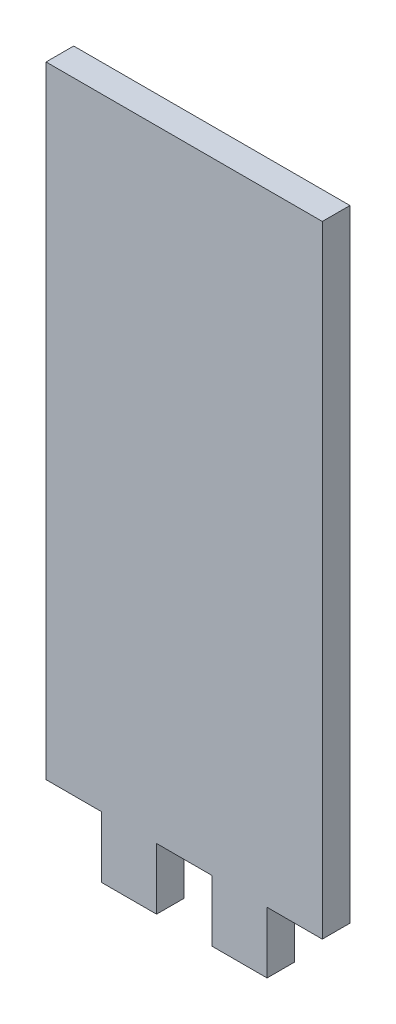
SolidWorks part; units mm, degrees
material "Акрил (Средняя-высокая ударопрочность)"
ref_plane "Спереди" through (0, 0, 0) normal (0, 0, 1) x (1, 0, 0)
ref_plane "Сверху" through (0, 0, 0) normal (0, 1, 0) x (1, 0, 0)
ref_plane "Справа" through (0, 0, 0) normal (1, 0, 0) x (0, 0, -1)
other "Configuration Table"
sketch "Эскиз1" plane through (0, 0, 0) normal (0, 0, 1) x (1, 0, 0)
  line L1 (10, -22.5) -> (6, -22.5)
  line L2 (10, -22.5) -> (10, 22.5)
  line L3 (10, 22.5) -> (-10, 22.5)
  line L4 (-10, -22.5) -> (-10, 22.5)
  line L5 (10, -22.5) -> (-10, 22.5) construction
  line L6 (10, 22.5) -> (-10, -22.5) construction
  line L11 (-6, -22.5) -> (-6, -26.9352)
  line L12 (-2, -26.9352) -> (-2, -22.5)
  line L16 (-6, -22.5) -> (-10, -22.5)
  line L17 (-2, -22.5) -> (2, -22.5)
  line L18 (2, -22.5) -> (2, -26.9352)
  line L19 (2, -26.9352) -> (6, -26.9352)
  line L20 (6, -26.9352) -> (6, -22.5)
  line L22 (-6, -26.9352) -> (-2, -26.9352)
  point P0 (0, 0)
  point P5 (0, -24)
  dimension "D1" = 4
  dimension "D2" = 45
  dimension "D3" = 20
extrude "Бобышка-Вытянуть1" add sketch "Эскиз1" along normal blind 2
